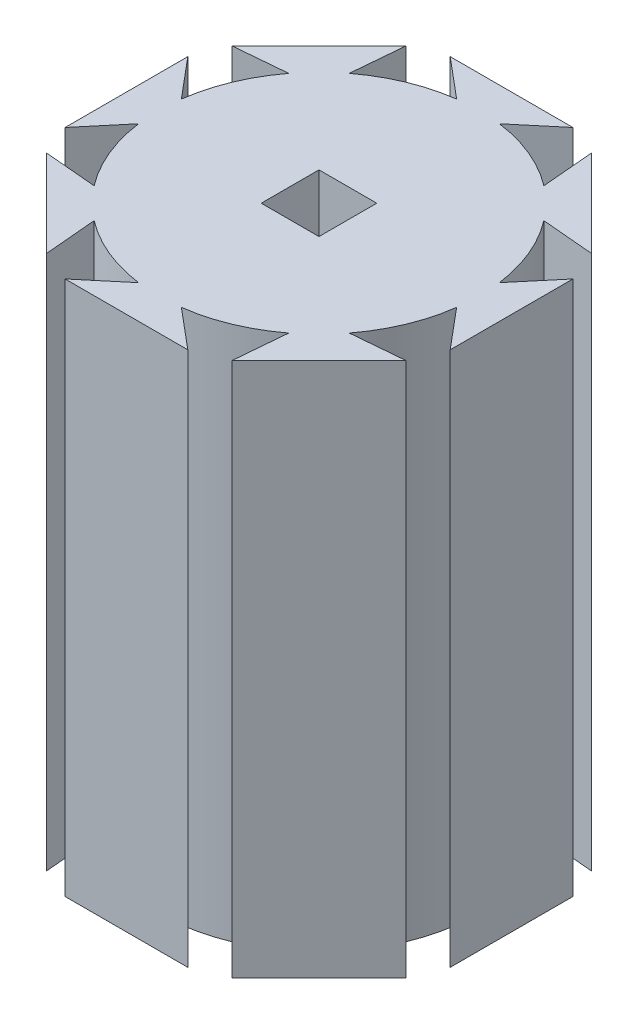
SolidWorks part; units mm, degrees
ref_plane "Front Plane" through (0, 0, 0) normal (0, 0, 1) x (1, 0, 0)
ref_plane "Top Plane" through (0, 0, 0) normal (0, 1, 0) x (1, 0, 0)
ref_plane "Right Plane" through (0, 0, 0) normal (1, 0, 0) x (0, 0, -1)
sketch "Sketch2" plane through (0, 0, 0) normal (0, 1, 0) x (1, 0, 0)
  line L1 (-3.429, -3.429) -> (3.429, -3.429)
  line L2 (-3.429, -3.429) -> (-3.429, 3.429)
  line L3 (-3.429, 3.429) -> (3.429, 3.429)
  line L4 (3.429, -3.429) -> (3.429, 3.429)
  line L5 (-3.429, -3.429) -> (3.429, 3.429) construction
  line L6 (-3.429, 3.429) -> (3.429, -3.429) construction
  circle A0 centre (0, 0) radius 19.05
  dimension "D1" = 38.1
  dimension "D2" = 6.858
extrude "Boss-Extrude1" add sketch "Sketch2" along normal blind 63.5
sketch "Sketch3" plane through (0, 0, 0) normal (0, 1, 0) x (1, 0, 0)
  line L0 (0, 19.05) -> (0, 22.86) construction
  line L1 (7.2833, 22.86) -> (-7.2833, 22.86)
  line L2 (-7.2833, 22.86) -> (-2.54, 18.8799)
  line L3 (7.2833, 22.86) -> (2.54, 18.8799)
  circle A0 centre (0, 0) radius 19.05 construction
  circle A1 centre (0, 0) radius 19.05
  point P10 (-3.3931, 12.2383)
  dimension "D1" = 40
  dimension "D2" = 3.81
  dimension "D3" = 2.54
extrude "Boss-Extrude2" add sketch "Sketch3" along normal up to surface (63.5 mm away) contours L0 A1 L3 L1 | A1 L0 L1 L2 up to face at (0, 63.5, 19.05)
pattern_circular "CirPattern1" count 8 over 360 about axis through (0, 0, 0) along (0, 1, 0) of "Boss-Extrude2"
